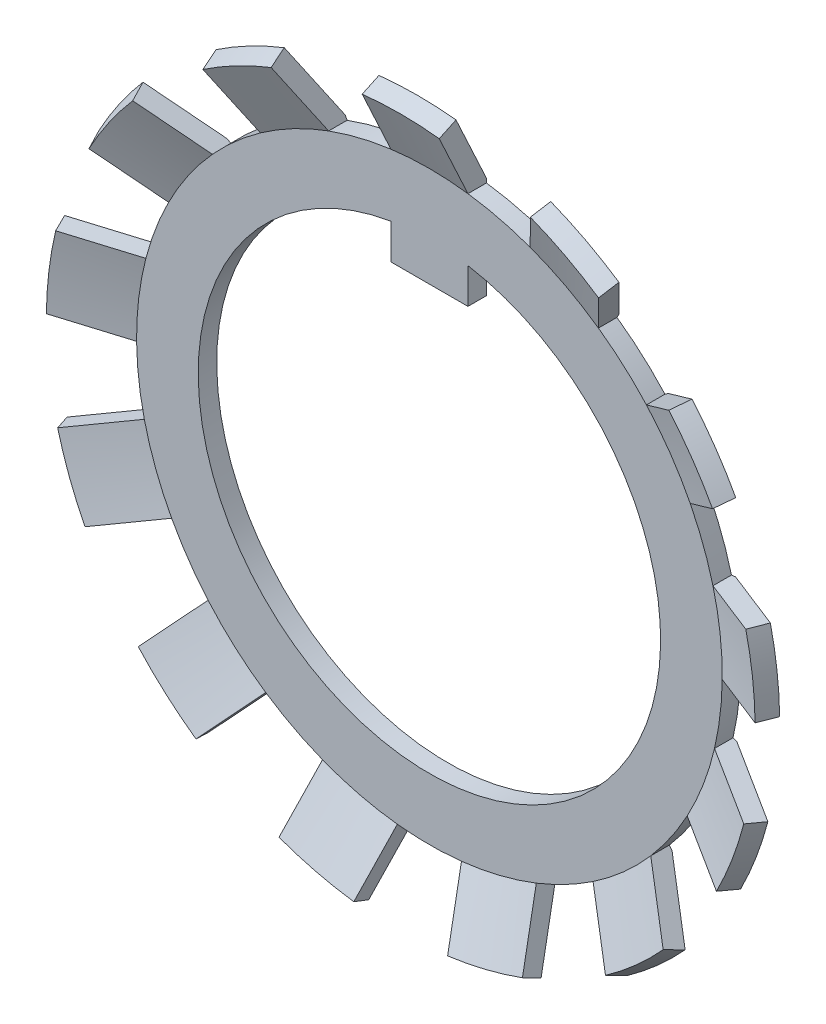
SolidWorks part; units mm, degrees
revolve "Base-Revolve" add sketch "Sketch1" angle 360 about L6
sketch "Sketch1" plane through (0, 0, 0) normal (1, 0, 0) x (0, 0, -1)
  line L0 (0, 15) -> (0, 19.266)
  line L1 (0, 19.266) -> (-1.9743, 23.5)
  line L2 (-1.2, 19) -> (-3.0619, 22.9929)
  line L3 (-1.2, 15) -> (-1.2, 19)
  line L4 (-3.0619, 22.9929) -> (-1.9743, 23.5)
  line L5 (-1.2, 15) -> (0, 15)
  line L6 (-14, 0) -> (12, 0) construction
  dimension "d3" = 30
  dimension "Tab Angle" = 25
  dimension "d5" = 47
  dimension "d4" = 38
  dimension "B1" = 1.2
ref_plane "Plane1" through (0, 0, 0) normal (0, 0, 1) x (1, 0, 0)
ref_plane "Plane2" through (0, 0, 0) normal (0, 1, 0) x (1, 0, 0)
ref_plane "Plane3" through (0, 0, 0) normal (1, 0, 0) x (0, 0, -1)
sketch "Sketch3" plane through (0, 0, 0) normal (0, 0, -1) x (-1, 0, 0)
  line L0 (0, 0) -> (0, 40) construction
  line L1 (0, 0) -> (-13.3684, 25.4713) construction
  line L2 (-2.5, 18.8348) -> (-2.5, 23.3666)
  line L3 (-6.5393, 17.8392) -> (-8.6454, 21.8519)
  line L4 (-2.5, 23.3666) -> (-8.6454, 21.8519) construction
  line L5 (0, 0) -> (-5.5727, 22.6093) construction
  circle A0 centre (0, 0) radius 19 construction
  circle A1 centre (0, 0) radius 23.5 construction
  arc A2 (-2.5, 18.8348) -> (-6.5393, 17.8392) centre (0, 0) ccw
  arc A3 (-2.5, 23.3666) -> (-8.6454, 21.8519) centre (0, 0) ccw
  dimension "D3" = 5
  dimension "D1" = 13.846
extrude "Cut-Extrude2" cut sketch "Sketch3" against normal through all
pattern_circular "CirPattern1" count 13 over 360 about axis through (0, 0, 0) along (0, 0, 1) of "Cut-Extrude2"
sketch "Sketch4" plane through (0, 0, 0) normal (0, 0, -1) x (-1, 0, 0)
  line L2 (-2.5, 14.7902) -> (-2.5, 12.5)
  line L3 (2.5, 12.5) -> (2.5, 14.7902)
  line L4 (-2.5, 12.5) -> (2.5, 12.5)
  line L7 (0, 0) -> (0, 22) construction
  line L9 (-2.5, 18.8348) -> (-2.5, 23.3666) construction
  circle A0 centre (0, 0) radius 15 construction
  circle A2 centre (0, 0) radius 15
  arc A3 (2.5, 14.7902) -> (-2.5, 14.7902) centre (0, 0) ccw
  dimension "M" = 27.5
  dimension "D2" = 0
extrude "Boss-Extrude1" add sketch "Sketch4" along normal up to surface (1.2 mm away)
equation "\"D1@Sketch3\" = (360/\"No Tabs@CirPattern1\")/2"
equation "\"D3@Sketch3\"=\"f@Sketch3\""
